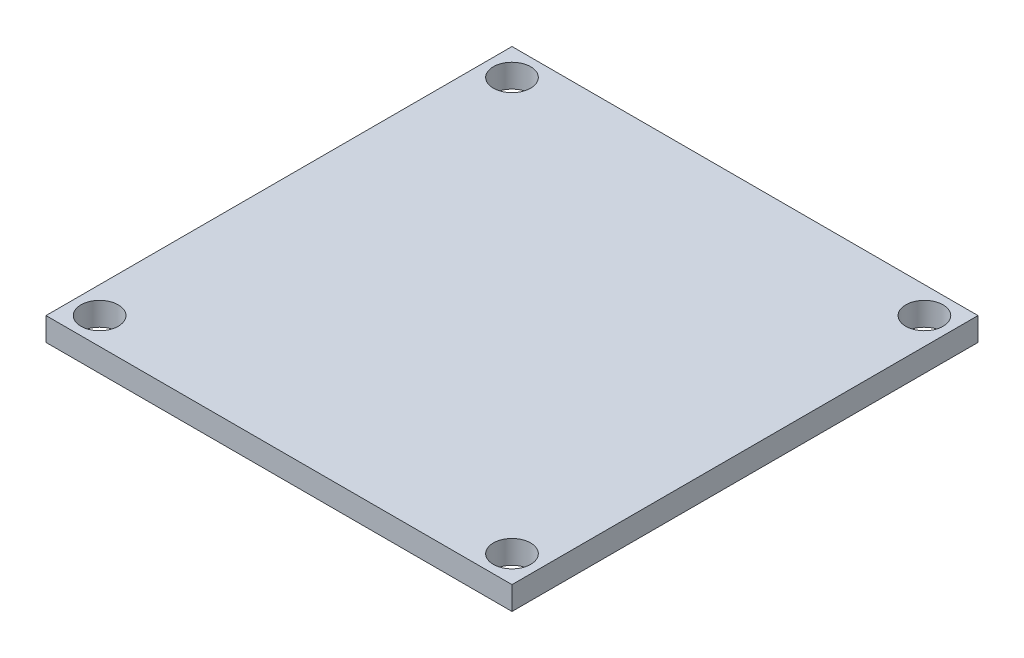
SolidWorks part; units mm, degrees
ref_plane "Front Plane" through (0, 0, 0) normal (0, 0, 1) x (1, 0, 0)
ref_plane "Top Plane" through (0, 0, 0) normal (0, 1, 0) x (1, 0, 0)
ref_plane "Right Plane" through (0, 0, 0) normal (1, 0, 0) x (0, 0, -1)
sketch "Sketch1" plane through (0, 0, 0) normal (0, 1, 0) x (1, 0, 0)
  line L0 (0, 0) -> (0, 20) construction
  line L1 (-20, 20) -> (20, 20)
  line L2 (-20, 20) -> (-20, -20)
  line L3 (-20, -20) -> (20, -20)
  line L4 (20, 20) -> (20, -20)
  line L5 (0, 0) -> (20, 0) construction
  dimension "D1" = 40
extrude "Boss-Extrude1" add sketch "Sketch1" along normal blind 2
sketch "Sketch2" plane through (0, 2, 0) normal (0, 1, 0) x (1, 0, 0)
  line L0 (0, 0) -> (0, 20) construction
  line L1 (20, 20) -> (-20, 20) construction
  line L2 (0, 0) -> (-20, 0) construction
  line L3 (-20, 20) -> (-20, -20) construction
  circle A0 centre (-17.7, 17.7) radius 1.6
  circle A1 centre (0, 0) radius 3 construction
  circle A2 centre (17.7, 17.7) radius 1.6
  circle A3 centre (17.7, -17.7) radius 1.6
  circle A4 centre (-17.7, -17.7) radius 1.6
  point P20 (0, 0)
  dimension "D3" = 3.2
  dimension "D4" = 6
  dimension "D1" = 17.7
  dimension "D2" = 17.7
  dimension "D5" = 4
extrude "Cut-Extrude1" cut sketch "Sketch2" against normal through all
